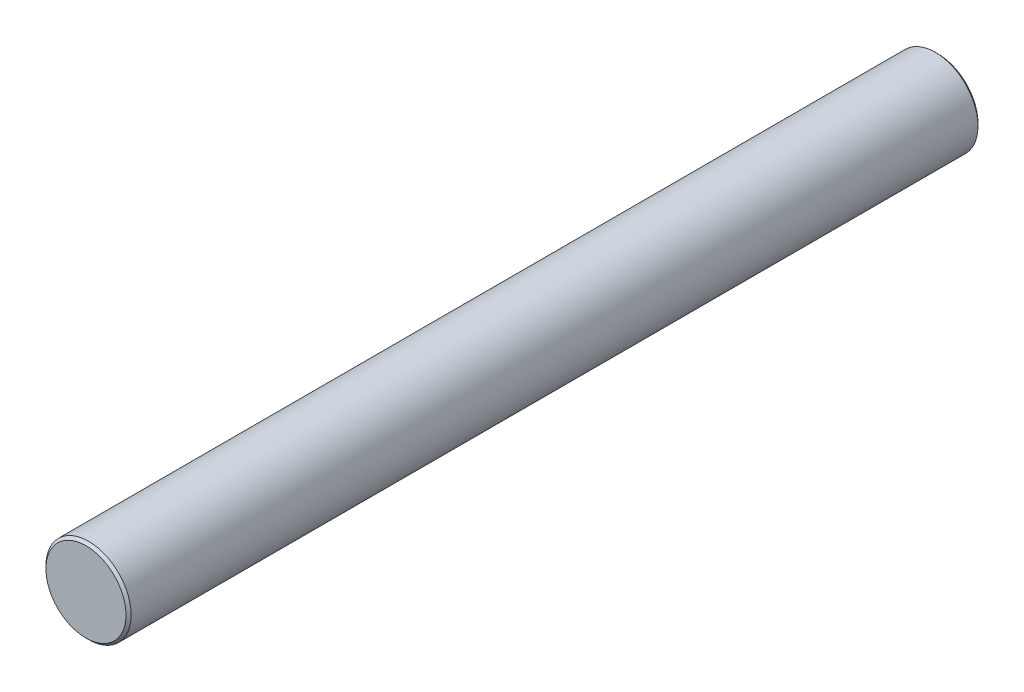
SolidWorks part; units mm, degrees
ref_plane "Front Plane" through (0, 0, 0) normal (0, 0, 1) x (1, 0, 0)
ref_plane "Top Plane" through (0, 0, 0) normal (0, 1, 0) x (1, 0, 0)
ref_plane "Right Plane" through (0, 0, 0) normal (1, 0, 0) x (0, 0, -1)
sketch "Sketch1" plane through (0, 0, 0) normal (0, 0, 1) x (1, 0, 0)
  circle A0 centre (0, 0) radius 5
extrude "Boss-Extrude1" add sketch "Sketch1" along normal mid plane 100
chamfer "Chamfer1" distance 0.3 angle 45 2 edges at (5, 0, -50) (5, 0, 50)
